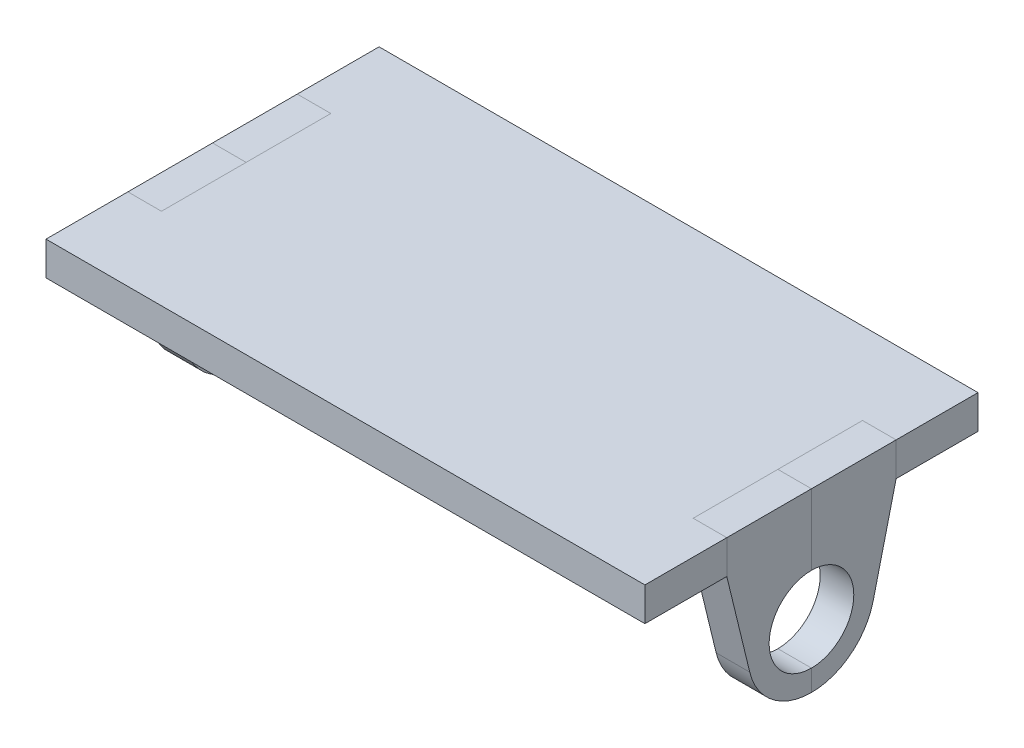
SolidWorks part; units mm, degrees
ref_plane "前视基准面" through (0, 0, 0) normal (0, 0, 1) x (1, 0, 0)
ref_plane "上视基准面" through (0, 0, 0) normal (0, 1, 0) x (1, 0, 0)
ref_plane "右视基准面" through (0, 0, 0) normal (1, 0, 0) x (0, 0, -1)
other "Configuration Table"
sketch "草图1" plane through (0, 0, 0) normal (0, 1, 0) x (1, 0, 0)
  line L1 (0, 0) -> (35, 0)
  line L3 (0, 62.94) -> (35, 62.94)
  line L5 (-18.175, 62.94) -> (95, 62.94)
  line L6 (41.35, 0) -> (95, 0)
  line L8 (41.35, 62.94) -> (95, 62.94)
  line L10 (-18.175, 62.94) -> (-18.175, 0)
  line L11 (-3.175, 0) -> (-18.175, 0)
  line L13 (-3.175, 62.94) -> (-18.175, 62.94)
  line L15 (-18.175, 0) -> (95, 0)
  line L16 (95, 62.94) -> (95, 0)
extrude "凸台-拉伸1" add sketch "草图1" along normal blind 6.35
sketch "草图2" plane through (95, 0, 0) normal (1, 0, 0) x (0, 0, -1)
  line L0 (31.47, -15) -> (31.47, 0) construction
  line L2 (15.47, 6.35) -> (47.47, 6.35)
  line L3 (62.94, 0) -> (0, 0) construction
  line L4 (62.94, 6.35) -> (0, 6.35) construction
  line L5 (15.47, 6.35) -> (19.6567, -17.1084)
  line L6 (47.47, 6.35) -> (43.2833, -17.1084)
  circle A0 centre (31.47, -15) radius 12
  circle A1 centre (31.47, -15) radius 8
  point P10 (31.47, 6.35)
  point P11 (31.47, 6.35)
  dimension "D1" = 32
  dimension "D2" = 15
sketch "草图4" plane through (0, 6.35, 0) normal (0, 1, 0) x (1, 0, 0)
  line L0 (-18.175, 62.94) -> (-18.175, 0) construction
  line L1 (-24.525, 15.47) -> (-11.825, 15.47)
  line L2 (-24.525, 15.47) -> (-24.525, 47.47)
  line L3 (-24.525, 47.47) -> (-11.825, 47.47)
  line L4 (-11.825, 15.47) -> (-11.825, 47.47)
  line L5 (-24.525, 15.47) -> (-11.825, 47.47) construction
  line L6 (-24.525, 47.47) -> (-11.825, 15.47) construction
  line L7 (95, 23.47) -> (95, 39.47) construction
  line L8 (101.35, 15.47) -> (88.65, 15.47)
  line L9 (101.35, 15.47) -> (101.35, 47.47)
  line L10 (101.35, 47.47) -> (88.65, 47.47)
  line L11 (88.65, 15.47) -> (88.65, 47.47)
  line L12 (101.35, 15.47) -> (88.65, 47.47) construction
  line L13 (101.35, 47.47) -> (88.65, 15.47) construction
  point P0 (-18.175, 31.47)
  point P7 (95, 31.47)
extrude "切除-拉伸1" cut sketch "草图4" against normal blind 16.35
sketch "草图5" plane through (95, 0, 0) normal (1, 0, 0) x (0, 0, -1)
  line L1 (15.47, 6.35) -> (47.47, 6.35) construction
  line L3 (15.47, 0) -> (15.47, 6.35)
  line L4 (15.47, 6.35) -> (47.47, 6.35)
  line L5 (47.47, 6.35) -> (47.47, 0)
  line L6 (47.47, 0) -> (43.1298, -17.8371)
  line L7 (15.47, 0) -> (19.8102, -17.8371)
  line L8 (31.47, -27) -> (31.47, 6.35)
  circle A1 centre (31.47, -15) radius 8
  circle A2 centre (31.47, -15) radius 8
  circle A3 centre (31.47, -15) radius 12
  circle A4 centre (31.47, -15) radius 12
  line M7 (15.47, 0) -> (15.47, 6.35)
  dimension "D1" = 0
  dimension "D2" = 0
extrude "凸台-拉伸2" add sketch "草图5" against normal up to surface (6.35 mm away) separate body contours A4 L6 L5 L4 L7 M7 | A4 A2
ref_plane "基准面1" through (38.4125, 0, 0) normal (-1, 0, 0) x (0, 0, 1)
mirror "镜向1" about plane through (38.4125, 0, 0) normal (-1, 0, 0) of bodies 110
mirror "镜向2" about plane through (25.1645, 0, -31.47) normal (0, 0, -1) of bodies 110 111
